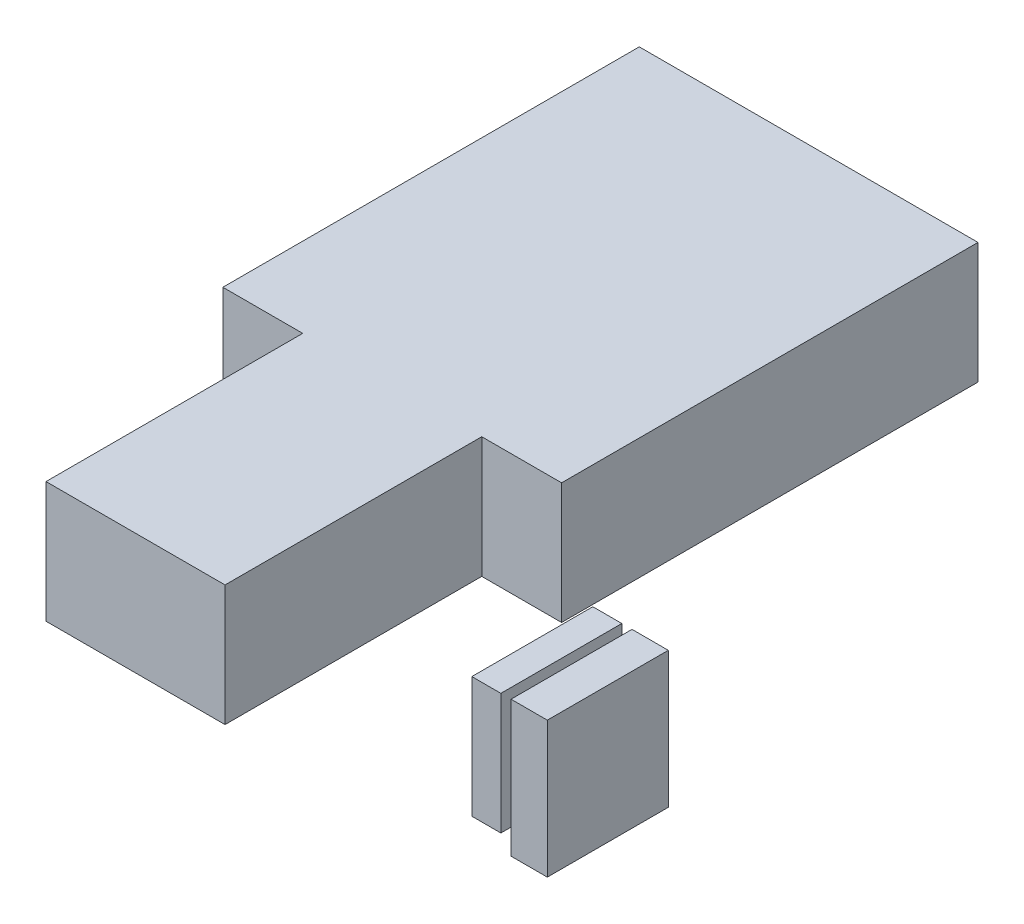
SolidWorks part; units mm, degrees
ref_plane "Front Plane" through (0, 0, 0) normal (0, 0, 1) x (1, 0, 0)
ref_plane "Top Plane" through (0, 0, 0) normal (0, 1, 0) x (1, 0, 0)
ref_plane "Right Plane" through (0, 0, 0) normal (1, 0, 0) x (0, 0, -1)
sketch "Sketch1" plane through (0, 0, 0) normal (1, 0, 0) x (0, 0, -1)
  line L1 (-12.5, 12.5) -> (12.5, 12.5)
  line L2 (-12.5, 12.5) -> (-12.5, -12.5)
  line L3 (-12.5, -12.5) -> (12.5, -12.5)
  line L4 (12.5, 12.5) -> (12.5, -12.5)
  line L5 (-12.5, 12.5) -> (12.5, -12.5) construction
  line L6 (-12.5, -12.5) -> (12.5, 12.5) construction
  point P0 (0, 0)
  dimension "D1" = 25
  dimension "D2" = 25
extrude "Boss-Extrude1" add sketch "Sketch1" along normal blind 6
ref_plane "Plane1" through (15.6, 0, 0) normal (-1, 0, 0) x (0, 0, 1)
sketch "Sketch3" plane through (15.6, 0, 0) normal (-1, 0, 0) x (0, 0, 1)
  line L0 (-12.5, 12.5) -> (12.5, 12.5)
  line L1 (12.5, 12.5) -> (12.5, -15.6)
  line L2 (12.5, -15.6) -> (-12.5, -15.6)
  line L3 (-12.5, -15.6) -> (-12.5, 12.5)
  dimension "D1" = 28.1
extrude "Boss-Extrude2" add sketch "Sketch3" along normal blind 7.5 separate body
sketch "Sketch5" plane through (0, -15.6, 0) normal (0, -1, 0) x (1, 0, 0)
  line L0 (8.1, 12.5) -> (20.6, 12.5)
  line L1 (15.6, 13.75) -> (15.6, -13.75) construction
  line L2 (20.6, 12.5) -> (20.6, -12.5)
  line L3 (8.1, -12.5) -> (20.6, -12.5)
  line L4 (20.6, 0) -> (44.6, 0)
  line L5 (44.6, 0) -> (44.6, 2.5)
  line L6 (44.6, 2.5) -> (20.6, 2.5)
  line L7 (44.6, 0) -> (44.6, -2.5)
  line L8 (44.6, -2.5) -> (20.6, -2.5)
  line L9 (20.6, -12.5) -> (32.6, -12.5)
  line L10 (32.6, -12.5) -> (32.6, -2.5)
  line L11 (8.1, -12.5) -> (8.1, -30)
  line L12 (8.1, -30) -> (58.1, -30)
  line L13 (58.1, -30) -> (58.1, 30)
  line L14 (58.1, 0) -> (44.6, 0)
  line L15 (8.1, 12.5) -> (8.1, 30)
  line L16 (8.1, 30) -> (58.1, 30)
  dimension "D1" = 5
  dimension "D2" = 2.5
  dimension "D3" = 24
  dimension "D4" = 2.5
  dimension "D5" = 12
  dimension "D6" = 50
  dimension "D7" = 30
sketch "Sketch6" plane through (0, -15.6, 0) normal (0, -1, 0) x (1, 0, 0)
  line L0 (8.1, 30) -> (58.1, 30) construction
  line L1 (8.1, 12.5) -> (8.1, 30) construction
  line L2 (58.1, -30) -> (58.1, 30) construction
  line L3 (8.1, -30) -> (58.1, -30) construction
  line L4 (8.1, -12.5) -> (8.1, -30) construction
  line L5 (20.6, -12.5) -> (32.6, -12.5) construction
  line L6 (8.1, -12.5) -> (20.6, -12.5) construction
  line L7 (32.6, -12.5) -> (32.6, -2.5) construction
  line L8 (44.6, -2.5) -> (20.6, -2.5) construction
  line L9 (44.6, 0) -> (44.6, -2.5) construction
  line L10 (44.6, 0) -> (44.6, 2.5) construction
  line L11 (44.6, 2.5) -> (20.6, 2.5) construction
  line L12 (20.6, 12.5) -> (20.6, -12.5) construction
  line L13 (8.1, 12.5) -> (20.6, 12.5) construction
  line L14 (8.1, 30) -> (58.1, 30)
  line L15 (8.1, 12.5) -> (8.1, 30)
  line L16 (58.1, -30) -> (58.1, 30)
  line L17 (8.1, -30) -> (58.1, -30)
  line L18 (8.1, -12.5) -> (8.1, -30)
  line L19 (20.6, -12.5) -> (32.6, -12.5)
  line L20 (8.1, -12.5) -> (20.6, -12.5)
  line L21 (32.6, -12.5) -> (32.6, -2.5)
  line L22 (44.6, -2.5) -> (32.6, -2.5)
  line L23 (44.6, 0) -> (44.6, -2.5)
  line L24 (44.6, 0) -> (44.6, 2.5)
  line L25 (44.6, 2.5) -> (20.6, 2.5)
  line L26 (20.6, 12.5) -> (20.6, 2.5)
  line L27 (8.1, 12.5) -> (20.6, 12.5)
sketch "Sketch7" plane through (0, -15.6, 0) normal (0, -1, 0) x (1, 0, 0)
  line L0 (8.1, 0) -> (84.1, 0)
  line L1 (8.1, -12.5) -> (8.1, 12.5) construction
  line L2 (84.1, -38) -> (84.1, 38)
  line L3 (84.1, 38) -> (8.1, 38)
  line L4 (8.1, 38) -> (8.1, -38)
  line L5 (8.1, -38) -> (84.1, -38)
  line L6 (46.1, 0) -> (46.1, -11.58)
  line L7 (-21, 12.5) -> (-21, -12.5)
  line L8 (15.6, 13.75) -> (15.6, -13.75) construction
  line L9 (8.1, 0) -> (-21, 0)
  circle A0 centre (46.1, 0) radius 3
  circle A1 centre (71.1902, 0) radius 3
  circle A2 centre (21.0098, 0) radius 3
  circle A3 centre (21.0098, 25) radius 3
  circle A4 centre (46.1, 25) radius 3
  circle A5 centre (71.1902, 25) radius 3
  circle A6 centre (71.1902, -25) radius 3
  circle A7 centre (46.1, -25) radius 3
  circle A8 centre (21.0098, -25) radius 3
  dimension "D3" = 6
  dimension "D4" = 6
  dimension "D1" = 76
  dimension "D2" = 38
  dimension "D6" = 36.6
  dimension "D5" = 2
sketch "Sketch8" plane through (0, -15.6, 0) normal (0, -1, 0) x (1, 0, 0)
  line L0 (-21, 0) -> (-23, 0)
  line L1 (-21, 12.5) -> (-21, -12.5) construction
  line L2 (-76.2, 12.7) -> (-50.8, 12.7)
  line L3 (-76.2, 12.7) -> (-76.2, -12.7)
  line L4 (-76.2, -12.7) -> (-50.8, -12.7)
  line L5 (-50.8, 12.7) -> (-50.8, -12.7)
  line L6 (-76.2, 12.7) -> (-50.8, -12.7) construction
  line L7 (-76.2, -12.7) -> (-50.8, 12.7) construction
  line L8 (-82, 18.5) -> (-45, 18.5)
  line L9 (-82, 18.5) -> (-82, -18.5)
  line L10 (-82, -18.5) -> (-45, -18.5)
  line L11 (-45, 18.5) -> (-45, -18.5)
  line L12 (-82, 18.5) -> (-45, -18.5) construction
  line L13 (-82, -18.5) -> (-45, 18.5) construction
  line L14 (-63.5, 0) -> (-45, 0)
  line L15 (-23, 0) -> (-45, 0)
  line L16 (-63.5, 0) -> (-63.5, 60)
  line L17 (-45.5, 60) -> (-81.5, 60)
  circle A0 centre (-49.0043, 14.4957) radius 1.5
  circle A1 centre (-49.0043, -14.4957) radius 1.5
  circle A2 centre (-77.9957, -14.4957) radius 1.5
  circle A3 centre (-77.9957, 14.4957) radius 1.5
  point P29 (-63.5, 0)
  dimension "D6" = 3
  dimension "D1" = 2
  dimension "D2" = 25.4
  dimension "D3" = 25.4
  dimension "D4" = 37
  dimension "D5" = 37
  dimension "D7" = 18.5
  dimension "D9" = 22
  dimension "D10" = 42.5
  dimension "D11" = 60
  dimension "D12" = 18
  dimension "D13" = 36
  dimension "D8" = 4
ref_plane "Plane2" through (0, 0, 60) normal (0, 0, 1) x (1, 0, 0)
sketch "Sketch9" plane through (0, 0, 60) normal (0, 0, 1) x (1, 0, 0)
  line L0 (-63.5, -15.6) -> (-63.5, -10.6)
  line L1 (-45.5, -15.6) -> (-81.5, -15.6) construction
  dimension "D1" = 5
sketch "Sketch11" plane through (0, -15.6, 0) normal (0, -1, 0) x (1, 0, 0)
  line L0 (-76.2, -12.7) -> (-50.8, 12.7) construction
  line L1 (-82, -18.5) -> (-45, -18.5)
  line L2 (-82, -18.5) -> (-82, 18.5)
  line L3 (-82, 18.5) -> (-45, 18.5)
  line L4 (-45, -18.5) -> (-45, 18.5)
  line L5 (-82, -18.5) -> (-45, 18.5) construction
  line L6 (-82, 18.5) -> (-45, -18.5) construction
  line L7 (-63.5, 0) -> (-12.9, 0)
  line L8 (-12.9, -18) -> (-12.9, 18) construction
  line L9 (-63.5, 0) -> (-63.5, -50.6)
  line L10 (-82, -18.5) -> (-82, -50.6)
  line L11 (-63.5, -50.6) -> (-98.5, -50.6)
  line L12 (-82, -34.55) -> (-98.5, -34.55)
  line L13 (-98.5, -34.55) -> (-98.5, -50.6)
  line L14 (-98.5, -50.6) -> (-98.5, -120.6)
  line L15 (-45, -18.5) -> (-45, -50.6)
  line L16 (-28.5, -34.55) -> (-28.5, -50.6)
  line L17 (-45, -34.55) -> (-28.5, -34.55)
  line L18 (-28.5, -50.6) -> (-28.5, -120.6)
  line L19 (-98.5, -120.6) -> (-28.5, -120.6)
  line L20 (-63.5, 0) -> (-153.5, 0)
  line L21 (-63.5, 0) -> (-63.5, 60)
  line L22 (-63.5, 60) -> (-56, 60)
  line L23 (-45.5, 60) -> (-81.5, 60) construction
  line L24 (-50.8, 12.7) -> (-50.8, 60)
  line L25 (-53, 60) -> (-53, 12.7)
  line L26 (-76.2, 12.7) -> (-50.8, 12.7) construction
  line L27 (-63.5, 60) -> (-71, 60)
  line L28 (-153.5, -25) -> (-153.5, 25)
  line L29 (-153.5, 10.5) -> (-76.2, 10.5)
  line L30 (-76.2, 12.7) -> (-76.2, -12.7) construction
  line L31 (-63.5, 60) -> (-63.5, 90)
  line L32 (-63.5, 90) -> (-40.06, 90)
  line L33 (-63.5, 85) -> (-40.06, 85)
  line L34 (-63.5, 90) -> (-56, 60)
  line L35 (-62.3, 85) -> (-62.3, 90)
  line L36 (-53, 60) -> (-53, 73)
  line L37 (-53, 73) -> (197, 73)
  line L38 (8.1, 38) -> (8.1, 55)
  line L39 (8.1, 55) -> (258.1, 55)
  line L40 (-187.3561, -135.5407) -> (-187.3561, 314.4593)
  line L41 (-187.3561, 314.4593) -> (262.6439, 314.4593)
  line L42 (262.6439, 314.4593) -> (262.6439, -135.5407)
  line L43 (262.6439, -135.5407) -> (-187.3561, -135.5407)
  line L44 (8.1, 38) -> (8.1, 66)
  line L45 (-83.5, 85) -> (-177.6161, 85)
  line L46 (-63.5, -120.6) -> (-63.5, -112.2425)
  line L47 (-83.5, 48) -> (-43.5, 48)
  line L48 (-63.5, 23) -> (-82, 23)
  line L49 (102.3839, -81.6) -> (102.3839, -125)
  line L50 (102.3839, -125) -> (-177.6161, -125)
  line L51 (102.3839, -81.6) -> (102.3839, 68.4)
  line L52 (102.3839, 68.4) -> (-43.5, 68.4)
  line L53 (-43.5, 32) -> (-43.5, 72) construction
  line L54 (-43.5, 68.4) -> (-43.5, 90)
  line L55 (-177.6161, -125) -> (-177.6161, 85)
  line L56 (-63.5, 23) -> (-45, 23)
  line L57 (-83.5, 56) -> (-43.5, 56) construction
  line L58 (-83.5, 46) -> (-43.5, 46)
  line L59 (-83.5, 72) -> (-83.5, 32) construction
  line L60 (-83.5, 46) -> (-83.5, 48)
  line L61 (-82, 23) -> (-82, 43)
  line L62 (-82, 43) -> (-45, 43)
  line L63 (-45, 43) -> (-45, 23)
  line L64 (-40.5, 0) -> (-40.5, -18.5)
  line L65 (-40.5, 0) -> (-40.5, 18.5)
  line L66 (-40.5, 18.5) -> (-20.5, 18.5)
  line L67 (-20.5, 18.5) -> (-20.5, -18.5)
  line L68 (-20.5, -18.5) -> (-40.5, -18.5)
  line L69 (-63.5, -23) -> (-82, -23)
  line L70 (-63.5, -23) -> (-45, -23)
  line L71 (-45, -23) -> (-45, -43)
  line L72 (-45, -43) -> (-82, -43)
  line L73 (-82, -43) -> (-82, -23)
  line L74 (-86.5, 0) -> (-86.5, 18.5)
  line L75 (-86.5, 0) -> (-86.5, -18.5)
  line L76 (-86.5, -18.5) -> (-106.5, -18.5)
  line L77 (-106.5, -18.5) -> (-106.5, 18.5)
  line L78 (-106.5, 18.5) -> (-86.5, 18.5)
  line L79 (-43.5, 48) -> (-43.5, 46)
  circle A0 centre (-49.0043, 14.4957) radius 1.5 construction
  circle A1 centre (-49.0043, -14.4957) radius 1.5 construction
  circle A2 centre (-77.9957, -14.4957) radius 1.5 construction
  circle A3 centre (-77.9957, 14.4957) radius 1.5 construction
  circle A4 centre (-49.0043, 14.4957) radius 1.5
  circle A5 centre (-49.0043, -14.4957) radius 1.5
  circle A6 centre (-77.9957, -14.4957) radius 1.5
  circle A7 centre (-77.9957, 14.4957) radius 1.5
  circle A8 centre (-53, 60) radius 0.5
  circle A9 centre (-93.5, -115.6) radius 1.5
  circle A10 centre (-33.5, -115.6) radius 1.5
  circle A11 centre (-93.5, -39.55) radius 1.5
  circle A12 centre (-33.5, -39.55) radius 1.5
  circle A13 centre (-63.5, 120) radius 1.5
  circle A14 centre (-63.5, 160) radius 1.5
  circle A15 centre (-23.5, 160) radius 1.5
  circle A16 centre (16.5, 160) radius 1.5
  circle A17 centre (-23.5, 120) radius 1.5
  circle A18 centre (56.5, 160) radius 1.5
  circle A19 centre (96.5, 160) radius 1.5
  circle A20 centre (-103.5, 160) radius 1.5
  circle A21 centre (16.5, 120) radius 1.5
  circle A22 centre (-143.5, 160) radius 1.5
  circle A23 centre (-183.5, 160) radius 1.5
  circle A24 centre (-63.5, 200) radius 1.5
  circle A25 centre (56.5, 120) radius 1.5
  circle A26 centre (-23.5, 200) radius 1.5
  circle A27 centre (16.5, 200) radius 1.5
  circle A28 centre (56.5, 200) radius 1.5
  circle A29 centre (96.5, 120) radius 1.5
  circle A30 centre (96.5, 200) radius 1.5
  circle A31 centre (-103.5, 200) radius 1.5
  circle A32 centre (-143.5, 200) radius 1.5
  circle A33 centre (-103.5, 120) radius 1.5
  circle A34 centre (-183.5, 200) radius 1.5
  circle A35 centre (-63.5, 240) radius 1.5
  circle A36 centre (-23.5, 240) radius 1.5
  circle A37 centre (-143.5, 120) radius 1.5
  circle A38 centre (16.5, 240) radius 1.5
  circle A39 centre (56.5, 240) radius 1.5
  circle A40 centre (96.5, 240) radius 1.5
  circle A41 centre (-183.5, 120) radius 1.5
  circle A42 centre (-103.5, 240) radius 1.5
  circle A43 centre (-143.5, 240) radius 1.5
  circle A44 centre (-183.5, 240) radius 1.5
  circle A45 centre (-63.5, 280) radius 1.5
  circle A46 centre (-23.5, 280) radius 1.5
  circle A47 centre (16.5, 280) radius 1.5
  circle A48 centre (56.5, 280) radius 1.5
  circle A49 centre (96.5, 280) radius 1.5
  circle A50 centre (-103.5, 280) radius 1.5
  circle A51 centre (-143.5, 280) radius 1.5
  circle A52 centre (-183.5, 280) radius 1.5
  circle A53 centre (-63.5, 300) radius 1.5
  circle A54 centre (-23.5, 300) radius 1.5
  circle A55 centre (16.5, 300) radius 1.5
  circle A56 centre (56.5, 300) radius 1.5
  circle A57 centre (96.5, 300) radius 1.5
  circle A58 centre (-103.5, 300) radius 1.5
  circle A59 centre (-143.5, 300) radius 1.5
  circle A60 centre (-183.5, 300) radius 1.5
  circle A61 centre (136.5, 160) radius 1.5
  circle A62 centre (136.5, 120) radius 1.5
  circle A63 centre (136.5, 200) radius 1.5
  circle A64 centre (136.5, 240) radius 1.5
  circle A65 centre (136.5, 280) radius 1.5
  circle A66 centre (136.5, 300) radius 1.5
  circle A67 centre (176.5, 160) radius 1.5
  circle A68 centre (176.5, 120) radius 1.5
  circle A69 centre (176.5, 200) radius 1.5
  circle A70 centre (176.5, 240) radius 1.5
  circle A71 centre (176.5, 280) radius 1.5
  circle A72 centre (176.5, 300) radius 1.5
  circle A73 centre (216.5, 160) radius 1.5
  circle A74 centre (216.5, 120) radius 1.5
  circle A75 centre (216.5, 200) radius 1.5
  circle A76 centre (216.5, 240) radius 1.5
  circle A77 centre (216.5, 280) radius 1.5
  circle A78 centre (216.5, 300) radius 1.5
  circle A79 centre (256.5, 160) radius 1.5
  circle A80 centre (256.5, 120) radius 1.5
  circle A81 centre (256.5, 200) radius 1.5
  circle A82 centre (256.5, 240) radius 1.5
  circle A83 centre (256.5, 280) radius 1.5
  circle A84 centre (256.5, 300) radius 1.5
  circle A85 centre (28.7088, 93.3723) radius 1.5 construction
  circle A86 centre (106.3325, 112.726) radius 1.5 construction
  circle A87 centre (28.7088, 93.3723) radius 1.5
  circle A88 centre (106.3325, 112.726) radius 1.5
  circle A89 centre (-80.5, 69) radius 1.5 construction
  circle A90 centre (-46.5, 107) radius 1.5
  circle A91 centre (-46.5, 107) radius 1.5
  circle A92 centre (-80.5, 107) radius 1.5
  circle A93 centre (-80.5, 107) radius 1.5
  circle A94 centre (-80.5, 78) radius 1.5
  circle A95 centre (-80.5, 78) radius 1.5
  circle A96 centre (-46.5, 78) radius 1.5
  circle A97 centre (-46.5, 78) radius 1.5
  circle A98 centre (-46.5, 69) radius 1.5 construction
  circle A99 centre (-46.5, 35) radius 1.5 construction
  circle A100 centre (-80.5, 35) radius 1.5 construction
  circle A101 centre (-80.5, 69) radius 1.5
  circle A102 centre (-46.5, 69) radius 1.5
  circle A103 centre (-46.5, 35) radius 1.5
  circle A104 centre (-80.5, 35) radius 1.5
  circle A105 centre (71.1902, -25) radius 3 construction
  circle A106 centre (21.0098, -25) radius 3 construction
  circle A107 centre (21.0098, 25) radius 3 construction
  circle A108 centre (71.1902, 25) radius 3 construction
  circle A109 centre (71.1902, -25) radius 3
  circle A110 centre (21.0098, -25) radius 3
  circle A111 centre (21.0098, 25) radius 3
  circle A112 centre (71.1902, 25) radius 3
  circle A113 centre (-128.5, 20) radius 1.5 construction
  circle A114 centre (-128.5, -20) radius 1.5 construction
  circle A115 centre (-168.5, -20) radius 1.5 construction
  circle A116 centre (-168.5, 20) radius 1.5 construction
  circle A117 centre (-128.5, 20) radius 1.5
  circle A118 centre (-128.5, -20) radius 1.5
  circle A119 centre (-168.5, -20) radius 1.5
  circle A120 centre (-168.5, 20) radius 1.5
  point P0 (-63.5, 0)
  point P24 (-63.5, -81.6)
  point P191 (-63.5, 0)
  dimension "D9" = 1
  dimension "D25" = 3
  dimension "D28" = 3
  dimension "D31" = 3
  dimension "D1" = 50.6
  dimension "D2" = 50.6
  dimension "D3" = 81.6
  dimension "D4" = 35
  dimension "D5" = 70
  dimension "D6" = 90
  dimension "D7" = 7.5
  dimension "D8" = 10.5
  dimension "D10" = 7.5
  dimension "D11" = 10.5
  dimension "D12" = 30
  dimension "D13" = 5
  dimension "D14" = 1.2
  dimension "D15" = 250
  dimension "D16" = 17
  dimension "D17" = 250
  dimension "D18" = 450
  dimension "D19" = 450
  dimension "D20" = 28
  dimension "D21" = 50
  dimension "D22" = 280
  dimension "D23" = 150
  dimension "D24" = 210
  dimension "D26" = 5
  dimension "D27" = 5
  dimension "D29" = 5
  dimension "D30" = 5
  dimension "D32" = 30
  dimension "D36" = 23
  dimension "D37" = 18.5
  dimension "D38" = 18.5
  dimension "D39" = 20
  dimension "D43" = 8
  dimension "D44" = 20
  dimension "D45" = 20
  dimension "D46" = 2
  dimension "D47" = 0
  dimension "D48" = 0
  dimension "D49" = 0
  dimension "D50" = 0
  dimension "D34" = 5
  dimension "D35" = 4
  dimension "D33" = 5
  dimension "D41" = 2
  dimension "D42" = 5
  dimension "D40" = 4
ref_plane "Plane3" through (0, -15.6, 0) normal (0, 1, 0) x (1, 0, 0)
sketch "Sketch12" plane through (0, -15.6, 0) normal (0, 1, 0) x (1, 0, 0)
  line L0 (-98.5, 120.6) -> (-28.5, 120.6)
  line L1 (-28.5, 120.6) -> (-28.5, 34.55)
  line L2 (-28.5, 34.55) -> (-45, 34.55)
  line L3 (-45, 34.55) -> (-45, -18.5)
  line L4 (-45, -18.5) -> (-82, -18.5)
  line L5 (-82, -18.5) -> (-82, 34.55)
  line L6 (-82, 34.55) -> (-98.5, 34.55)
  line L7 (-98.5, 34.55) -> (-98.5, 120.6)
extrude "Boss-Extrude3" add sketch "Sketch12" along normal blind 25 separate body
sketch "Sketch14" plane through (0, 9.4, 0) normal (0, 1, 0) x (1, 0, 0)
  line L0 (-98.5, 81.6) -> (-28.5, 81.6)
  line L1 (-98.5, 50.6) -> (-98.5, 120.6) construction
  line L2 (-28.5, 50.6) -> (-28.5, 120.6) construction
  line L3 (-98.5, 71.6) -> (-28.5, 71.6)
  line L4 (-63.5, 76.6) -> (-63.5, 81.6)
  line L5 (-98.5, 76.6) -> (-28.5, 76.6)
  line L6 (-82, 18.5) -> (-45, 18.5)
  line L7 (-45, 18.5) -> (-45, -18.5)
  line L8 (-45, -18.5) -> (-82, -18.5)
  line L9 (-82, -18.5) -> (-82, 18.5)
  point P12 (-63.5, 71.6)
  point P13 (-63.5, 76.6)
  point P14 (-63.5, 81.6)
  dimension "D1" = 10
ref_plane "Plane4" through (-153.5, 0, 0) normal (1, 0, 0) x (0, 0, -1)
sketch "Sketch16" plane through (-153.5, 0, 0) normal (1, 0, 0) x (0, 0, -1)
  line L0 (0, 51.8) -> (0, 26.4)
  line L1 (12.7, 51.8) -> (-12.7, 51.8) construction
  line L2 (18.5, 26.4) -> (-18.5, 26.4) construction
  line L3 (0, 26.4) -> (0, -15.6)
  line L4 (0, 39.1) -> (-3.6561, 39.1)
  line L6 (-10.5, -15.6) -> (-10.5, 39.1)
  circle A0 centre (0, 39.1) radius 7.5
  circle A1 centre (-10.5, 39.1) radius 0.5
  dimension "D2" = 15
  dimension "D3" = 1
  dimension "D1" = 54.7
  dimension "D4" = 54.7
  dimension "D5" = 10.5
sketch "Sketch17" plane through (0, 9.4, 0) normal (0, 1, 0) x (1, 0, 0)
  line L0 (-98, 81.6) -> (-98, 120.6)
  line L1 (-98, 81.6) -> (-93, 81.6) construction
  line L2 (-98.5, 120.6) -> (-28.5, 120.6) construction
  line L3 (-101, 81.6) -> (-101, 120.6)
  line L4 (-101, 120.6) -> (-26, 120.6)
  line L5 (-26, 120.6) -> (-26, 81.6)
  line L6 (-26, 81.6) -> (-26, 61.9489)
  line L7 (-26, 61.9489) -> (-101, 61.9489)
  line L8 (-101, 61.9489) -> (-101, 81.6)
